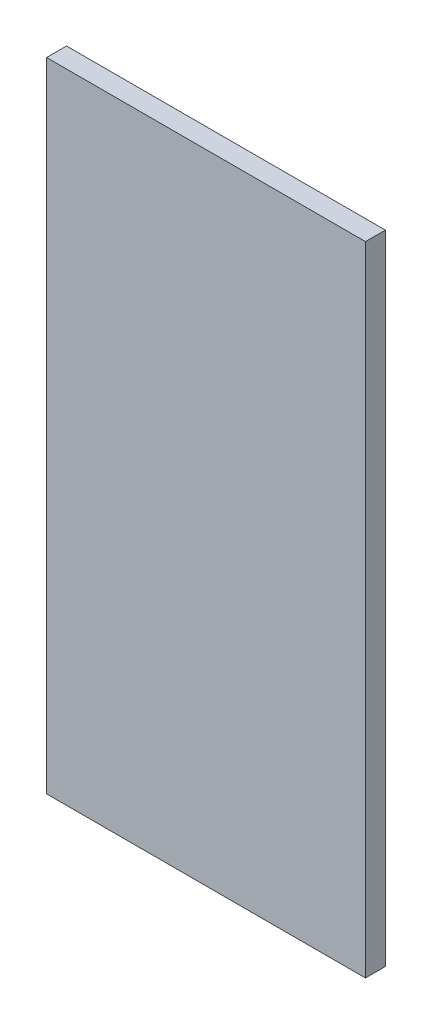
SolidWorks part; units mm, degrees
material "AISI 4340 Steel, normalized"
ref_plane "Front Plane" through (0, 0, 0) normal (0, 0, 1) x (1, 0, 0)
ref_plane "Top Plane" through (0, 0, 0) normal (0, 1, 0) x (1, 0, 0)
ref_plane "Right Plane" through (0, 0, 0) normal (1, 0, 0) x (0, 0, -1)
sketch "Sketch1" plane through (0, 0, 0) normal (0, 0, 1) x (1, 0, 0)
  line L1 (-12.7, 25.4) -> (12.7, 25.4)
  line L2 (-12.7, 25.4) -> (-12.7, -25.4)
  line L3 (-12.7, -25.4) -> (12.7, -25.4)
  line L4 (12.7, 25.4) -> (12.7, -25.4)
  line L5 (-12.7, 25.4) -> (12.7, -25.4) construction
  line L6 (-12.7, -25.4) -> (12.7, 25.4) construction
  point P0 (0, 0)
  dimension "D1" = 50.8
  dimension "D2" = 25.4
extrude "Boss-Extrude1" add sketch "Sketch1" along normal blind 1.5875
